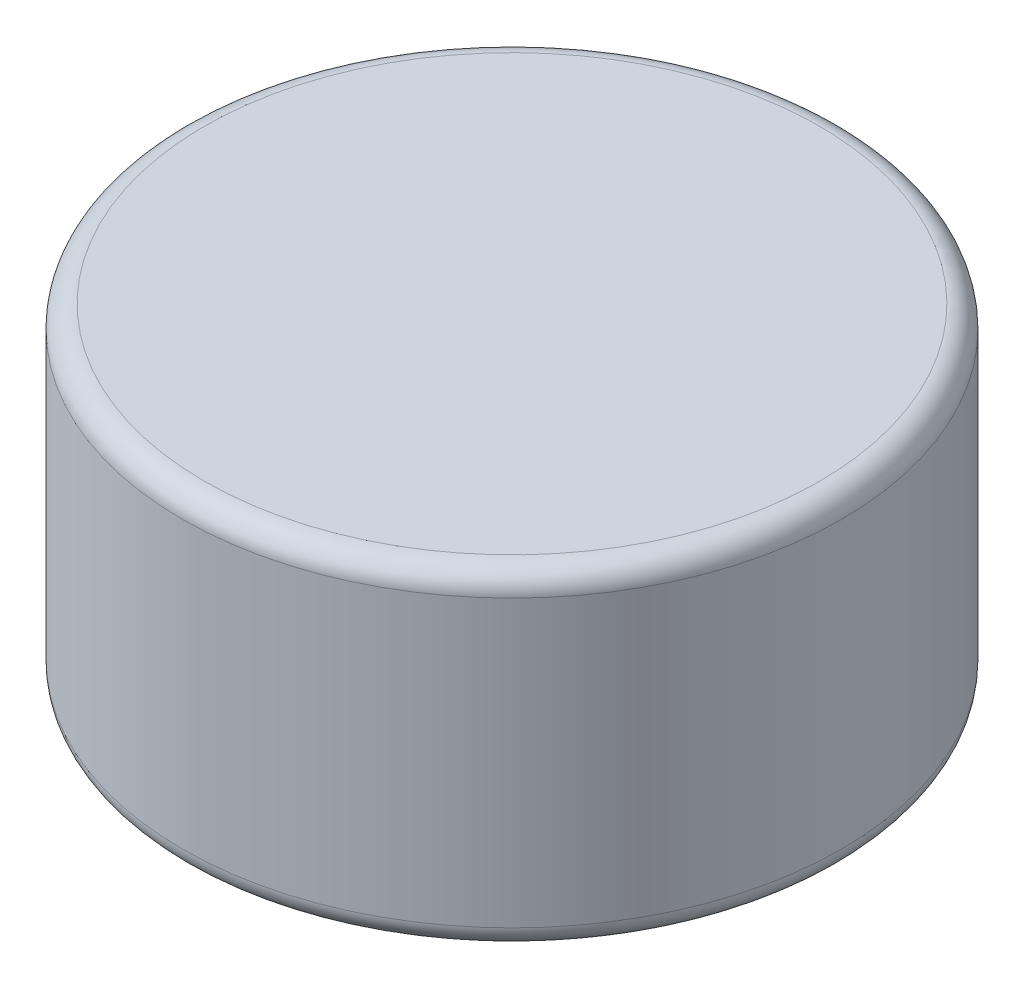
SolidWorks part; units mm, degrees
material "Custom Plastic"
ref_plane "Front Plane" through (0, 0, 0) normal (0, 0, 1) x (1, 0, 0)
ref_plane "Top Plane" through (0, 0, 0) normal (0, 1, 0) x (1, 0, 0)
ref_plane "Right Plane" through (0, 0, 0) normal (1, 0, 0) x (0, 0, -1)
sketch "Sketch1" plane through (0, 0, 0) normal (0, 1, 0) x (1, 0, 0)
  circle A0 centre (0, 0) radius 15
extrude "Boss-Extrude1" add sketch "Sketch1" along normal blind 15
fillet "Fillet1" radius 1 2 edges at (0, 15, 15) (0, 0, 15)
